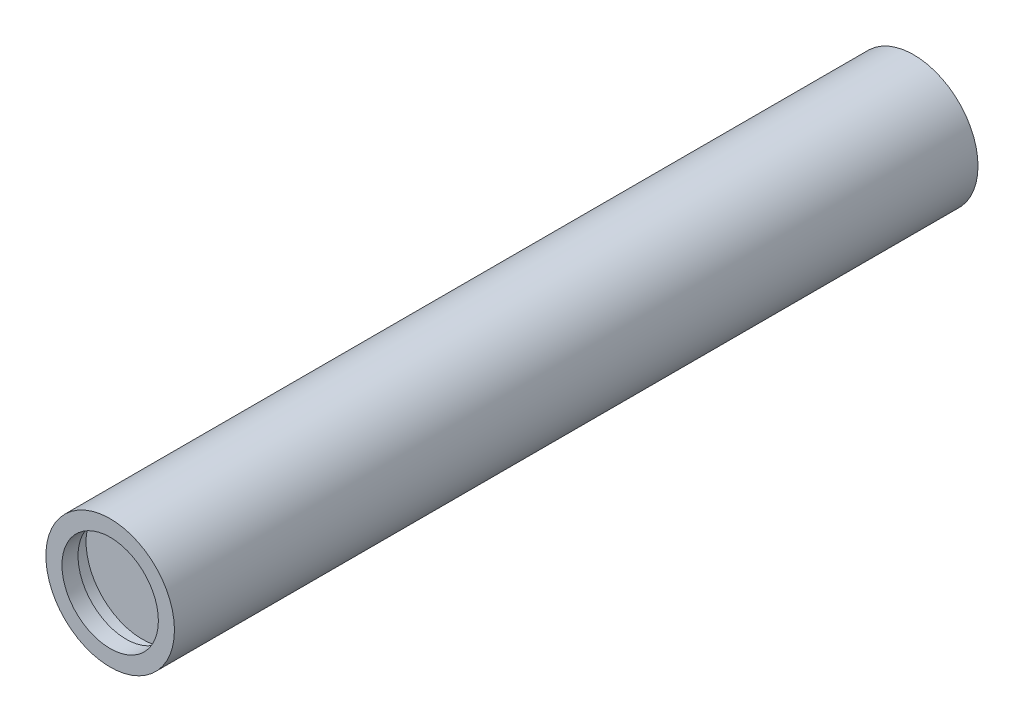
SolidWorks part; units mm, degrees
ref_plane "Front Plane" through (0, 0, 0) normal (0, 0, 1) x (1, 0, 0)
ref_plane "Top Plane" through (0, 0, 0) normal (0, 1, 0) x (1, 0, 0)
ref_plane "Right Plane" through (0, 0, 0) normal (1, 0, 0) x (0, 0, -1)
sketch "Sketch1" plane through (0, 0, 0) normal (0, 0, 1) x (1, 0, 0)
  circle A0 centre (0, 0) radius 40
  point P0 (0, 0)
  dimension "D1" = 80
extrude "Boss-Extrude1" add sketch "Sketch1" along normal blind 500
sketch "Sketch2" plane through (0, 0, 500) normal (0, 0, -1) x (-1, 0, 0)
  circle A0 centre (0, 0) radius 30
  dimension "D1" = 60
extrude "Cut-Extrude1" cut sketch "Sketch2" along normal blind 10
sketch "Sketch3" plane through (0, 0, 490) normal (0, 0, 1) x (1, 0, 0)
  circle A2 centre (0, 0) radius 35
  circle A3 centre (0, 0) radius 35
  dimension "D1" = 5
extrude "Cut-Extrude2" cut sketch "Sketch3" against normal blind 10
